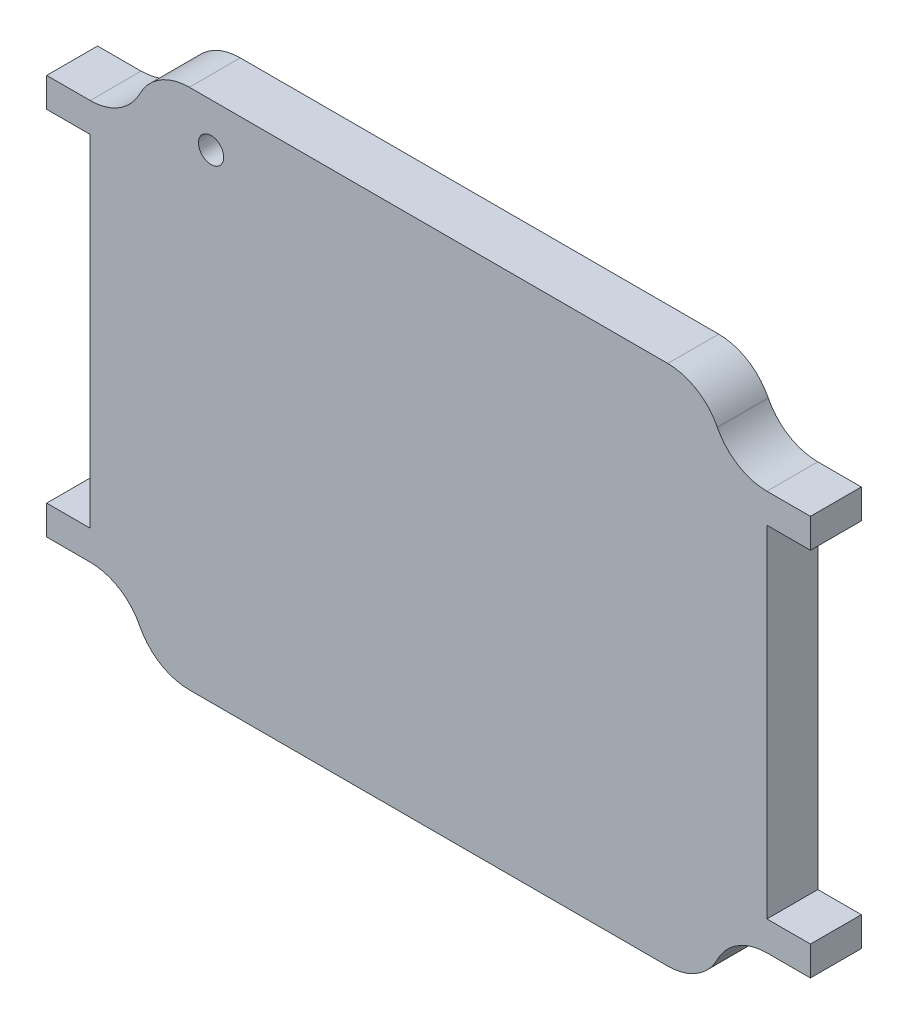
SolidWorks part; units mm, degrees
material "Acrylic (Medium-high impact)"
ref_plane "Front Plane" through (0, 0, 0) normal (0, 0, 1) x (1, 0, 0)
ref_plane "Top Plane" through (0, 0, 0) normal (0, 1, 0) x (1, 0, 0)
ref_plane "Right Plane" through (0, 0, 0) normal (1, 0, 0) x (0, 0, -1)
sketch "Sketch1" plane through (0, 0, 0) normal (0, 0, 1) x (1, 0, 0)
  line L0 (-1000, 0) -> (49000, 0) construction
  line L1 (0, -1000) -> (0, 49000) construction
  line L2 (-38.9, 19.6) -> (-38.9, -19.6)
  line L3 (-38.9, 19.6) -> (-43.9, 19.6)
  line L4 (-43.9, 19.6) -> (-43.9, 22.98)
  line L5 (-43.9, 22.98) -> (-38.9, 22.98)
  line L6 (-43.9, -22.98) -> (-38.9, -22.98)
  line L7 (-43.9, -19.6) -> (-43.9, -22.98)
  line L8 (-38.9, -19.6) -> (-43.9, -19.6)
  line L9 (-27.5, 30) -> (27.5, 30)
  line L10 (-38.9, 29.3632) -> (-27.5, 23.6168) construction
  line L11 (-27.5, -30) -> (27.5, -30)
  line L12 (43.9, -22.98) -> (38.9, -22.98)
  line L13 (43.9, -19.6) -> (43.9, -22.98)
  line L14 (38.9, -19.6) -> (43.9, -19.6)
  line L15 (38.9, 19.6) -> (38.9, -19.6)
  line L16 (38.9, 19.6) -> (43.9, 19.6)
  line L17 (43.9, 19.6) -> (43.9, 22.98)
  line L18 (43.9, 22.98) -> (38.9, 22.98)
  arc A0 (-38.9, 22.98) -> (-33.2, 26.49) centre (-38.9, 29.3632) ccw
  arc A1 (-33.2, 26.49) -> (-27.5, 30) centre (-27.5, 23.6168) cw
  arc A2 (-33.2, -26.49) -> (-27.5, -30) centre (-27.5, -23.6168) ccw
  arc A3 (-38.9, -22.98) -> (-33.2, -26.49) centre (-38.9, -29.3632) cw
  arc A4 (33.2, -26.49) -> (27.5, -30) centre (27.5, -23.6168) cw
  arc A5 (38.9, -22.98) -> (33.2, -26.49) centre (38.9, -29.3632) ccw
  arc A6 (38.9, 22.98) -> (33.2, 26.49) centre (38.9, 29.3632) cw
  arc A7 (33.2, 26.49) -> (27.5, 30) centre (27.5, 23.6168) ccw
  circle A8 centre (-25, 25) radius 1.45
  point P4 (-38.9, 0)
  point P16 (0, 30)
  point P17 (-33.2, 26.49)
  dimension "D7" = 2.9
  dimension "D1" = 30
  dimension "D2" = 39.2
  dimension "D3" = 3.38
  dimension "D4" = 5
  dimension "D5" = 38.9
  dimension "D6" = 55
  dimension "D8" = 25
  dimension "D9" = 25
extrude "Boss-Extrude1" add sketch "Sketch1" along normal blind 5.85
